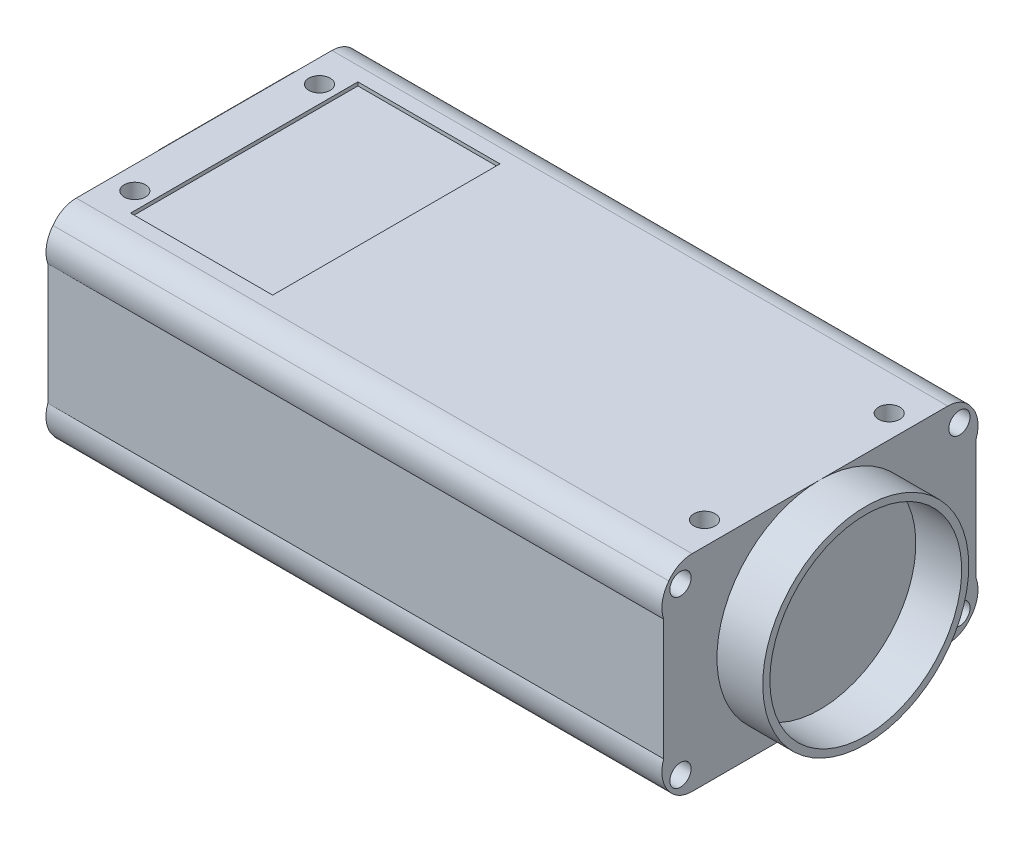
SolidWorks part; units mm, degrees
ref_plane "Front Plane" through (0, 0, 0) normal (0, 0, 1) x (1, 0, 0)
ref_plane "Top Plane" through (0, 0, 0) normal (0, 1, 0) x (1, 0, 0)
ref_plane "Right Plane" through (0, 0, 0) normal (1, 0, 0) x (0, 0, -1)
sketch "Croquis3" plane through (0, 0, 0) normal (1, 0, 0) x (0, 0, -1)
  line L1 (4, 0) -> (40, 0)
  line L2 (0, 5.979) -> (0, 23.021)
  line L3 (4, 29) -> (40, 29)
  line L4 (44, 5.979) -> (44, 23.021)
  arc A0 (40, 29) -> (43.2713, 27.3018) centre (40, 25) cw
  arc A1 (40, 0) -> (43.2713, 1.6982) centre (40, 4) ccw
  arc A2 (4, 0) -> (0.7287, 1.6982) centre (4, 4) cw
  arc A3 (0.7287, 27.3018) -> (4, 29) centre (4, 25) cw
  arc A4 (0.7287, 27.3018) -> (0, 23.021) centre (4.25, 24.5) ccw
  arc A5 (0.7287, 1.6982) -> (0, 5.979) centre (4.25, 4.5) cw
  arc A6 (43.2713, 1.6982) -> (44, 5.979) centre (39.75, 4.5) ccw
  arc A7 (43.2713, 27.3018) -> (44, 23.021) centre (39.75, 24.5) cw
  point P12 (0, 0)
  dimension "D2" = 4
extrude "Saliente-Extruir2" add sketch "Croquis3" along normal blind 86.7
sketch "Croquis4" plane through (86.7, 0, 0) normal (1, 0, 0) x (0, 0, -1)
  circle A0 centre (2.3643, 26.1509) radius 1.5
  circle A1 centre (41.6357, 26.1509) radius 1.5
  circle A2 centre (41.6357, 2.8491) radius 1.5
  circle A3 centre (2.3643, 2.8491) radius 1.5
extrude "Cortar-Extruir1" cut sketch "Croquis4" against normal blind 4
sketch "Croquis5" plane through (86.7, 0, 0) normal (1, 0, 0) x (0, 0, -1)
  circle A0 centre (22, 14.5) radius 14.5
  circle A1 centre (22, 14.5) radius 13.5
extrude "Saliente-Extruir3" add sketch "Croquis5" along normal blind 6.45
sketch "Croquis6" plane through (0, 29, 0) normal (0, 1, 0) x (1, 0, 0)
  line L2 (93.15, 7.5) -> (93.15, 36.5) construction
  circle A0 centre (83.45, 35) radius 1.5
  circle A1 centre (83.45, 9) radius 1.5
  circle A2 centre (3.25, 9) radius 1.5
  circle A3 centre (3.25, 35) radius 1.5
  dimension "D1" = 26
  dimension "D2" = 9
  dimension "D3" = 9
  dimension "D4" = 9.7
extrude "Cortar-Extruir2" cut sketch "Croquis6" against normal blind 3.5
sketch "Croquis8" plane through (0, 29, 0) normal (0, 1, 0) x (1, 0, 0)
  line L1 (5.6549, 38) -> (25.6549, 38)
  line L2 (5.6549, 38) -> (5.6549, 6)
  line L3 (5.6549, 6) -> (25.6549, 6)
  line L4 (25.6549, 38) -> (25.6549, 6)
  circle A0 centre (3.25, 35) radius 1.5 construction
  dimension "D3" = 3
  dimension "D1" = 20
  dimension "D2" = 32
extrude "Cortar-Extruir3" cut sketch "Croquis8" against normal blind 0.5
sketch "Croquis10" plane through (0, 0, 0) normal (-1, 0, 0) x (0, 0, 1)
  line L0 (-4, 0) -> (-40, 0) construction
  line L1 (-44, 5.979) -> (-44, 23.021) construction
  circle A0 centre (-30.5, 6.1) radius 1
  circle A1 centre (-30.5, 26.1) radius 1
  dimension "D1" = 20
  dimension "D2" = 6.1
  dimension "D3" = 13.5
extrude "Cortar-Extruir6" cut sketch "Croquis10" against normal blind 4.5
sketch "Croquis11" plane through (0, 0, 0) normal (-1, 0, 0) x (0, 0, 1)
  circle A2 centre (-41.6357, 26.1509) radius 1.5
  circle A3 centre (-41.6357, 2.8491) radius 1.5
  circle A4 centre (-2.3643, 2.8491) radius 1.5
  circle A5 centre (-2.3643, 26.1509) radius 1.5
extrude "Cortar-Extruir7" cut sketch "Croquis11" against normal blind 4.5
sketch "Croquis12" plane through (0, 0, 0) normal (-1, 0, 0) x (0, 0, 1)
  line L0 (-4, 0) -> (-40, 0) construction
  line L1 (-20.8558, 23.7) -> (-40.1442, 23.7)
  line L2 (-20.8558, 23.7) -> (-20.8558, 7.1)
  line L3 (-20.8558, 7.1) -> (-40.1442, 7.1)
  line L4 (-40.1442, 23.7) -> (-40.1442, 7.1)
  line L5 (-20.8558, 23.7) -> (-40.1442, 7.1) construction
  line L6 (-20.8558, 7.1) -> (-40.1442, 23.7) construction
  circle A0 centre (-30.5, 6.1) radius 1 construction
  point P0 (-30.5, 15.4)
  dimension "D1" = 15.4
  dimension "D2" = 1
extrude "Saliente-Extruir4" add sketch "Croquis12" along normal blind 5.35
sketch "Croquis13" plane through (-5.35, 0, 0) normal (-1, 0, 0) x (0, 0, 1)
  line L0 (-20.8558, 23.7) -> (-40.1442, 23.7) construction
  line L1 (-39.4893, 22.95) -> (-21.4893, 22.95)
  line L2 (-39.4893, 22.95) -> (-39.4893, 7.85)
  line L3 (-39.4893, 7.85) -> (-21.4893, 7.85)
  line L4 (-21.4893, 22.95) -> (-21.4893, 7.85)
  line L5 (-39.4893, 22.95) -> (-21.4893, 7.85) construction
  line L6 (-39.4893, 7.85) -> (-21.4893, 22.95) construction
  line L8 (-40.1442, 7.1) -> (-20.8558, 7.1) construction
  point P0 (-30.4893, 15.4)
  dimension "D1" = 18
  dimension "D2" = 0.75
  dimension "D3" = 0.75
extrude "Cortar-Extruir8" cut sketch "Croquis13" against normal blind 4.35
sketch "Croquis14" plane through (-1, 0, 0) normal (-1, 0, 0) x (0, 0, 1)
  line L1 (-35.5, 17.9) -> (-25.5, 17.9)
  line L2 (-35.5, 17.9) -> (-35.5, 12.9)
  line L3 (-35.5, 12.9) -> (-25.5, 12.9)
  line L4 (-25.5, 17.9) -> (-25.5, 12.9)
  line L5 (-35.5, 17.9) -> (-25.5, 12.9) construction
  line L6 (-35.5, 12.9) -> (-25.5, 17.9) construction
  circle A0 centre (-30.5, 26.1) radius 1 construction
  point P0 (-30.5, 15.4)
  dimension "D1" = 10
  dimension "D2" = 0
  dimension "D3" = 5
extrude "Cortar-Extruir9" cut sketch "Croquis14" against normal blind 1
sketch "Croquis15" plane through (0, 0, 0) normal (-1, 0, 0) x (0, 0, 1)
  line L0 (-4, 0) -> (-40, 0) construction
  circle A0 centre (-11.119, 15.6) radius 8
  dimension "D1" = 15.6
extrude "Cortar-Extruir10" cut sketch "Croquis15" against normal blind 3
sketch "Croquis16" plane through (3, 0, 0) normal (-1, 0, 0) x (0, 0, 1)
  circle A0 centre (-11.119, 15.6) radius 7
  circle A1 centre (-11.119, 15.6) radius 6
extrude "Saliente-Extruir5" add sketch "Croquis16" along normal blind 0.5 contours A1 | A0
sketch "Croquis17" plane through (3, 0, 0) normal (-1, 0, 0) x (0, 0, 1)
  circle A0 centre (-11.0258, 18.6) radius 0.5
  circle A1 centre (-11.119, 15.6) radius 6 construction
  circle A2 centre (-9.1193, 17.8382) radius 0.5
  circle A3 centre (-8.1484, 16.0292) radius 0.5
  circle A4 centre (-8.5675, 14.0193) radius 0.5
  circle A5 centre (-10.1805, 12.749) radius 0.5
  circle A6 centre (-12.2327, 12.8128) radius 0.5
  circle A7 centre (-13.7637, 14.1807) radius 0.5
  circle A8 centre (-14.0573, 16.2127) radius 0.5
  circle A9 centre (-12.976, 17.958) radius 0.5
  circle A11 centre (-11.985, 16.1) radius 0.5
  circle A12 centre (-10.253, 16.1) radius 0.5
  circle A13 centre (-11.119, 14.6) radius 0.5
  point P23 (-11.119, 15.6)
  dimension "D1" = 3
  dimension "D2" = 9
extrude "Cortar-Extruir12" cut sketch "Croquis17" against normal blind 1.5
sketch "Croquis18" plane through (0, 0, 0) normal (0, -1, 0) x (1, 0, 0)
  line L0 (93.15, -36.5) -> (93.15, -7.5) construction
  circle A0 centre (83.45, -8.3777) radius 1.5
  circle A1 centre (83.45, -34.3777) radius 1.5
  circle A2 centre (3.25, -34.3777) radius 1.5
  circle A3 centre (3.25, -8.3777) radius 1.5
  dimension "D1" = 26
  dimension "D2" = 9.7
extrude "Cortar-Extruir13" cut sketch "Croquis18" against normal blind 3.5
